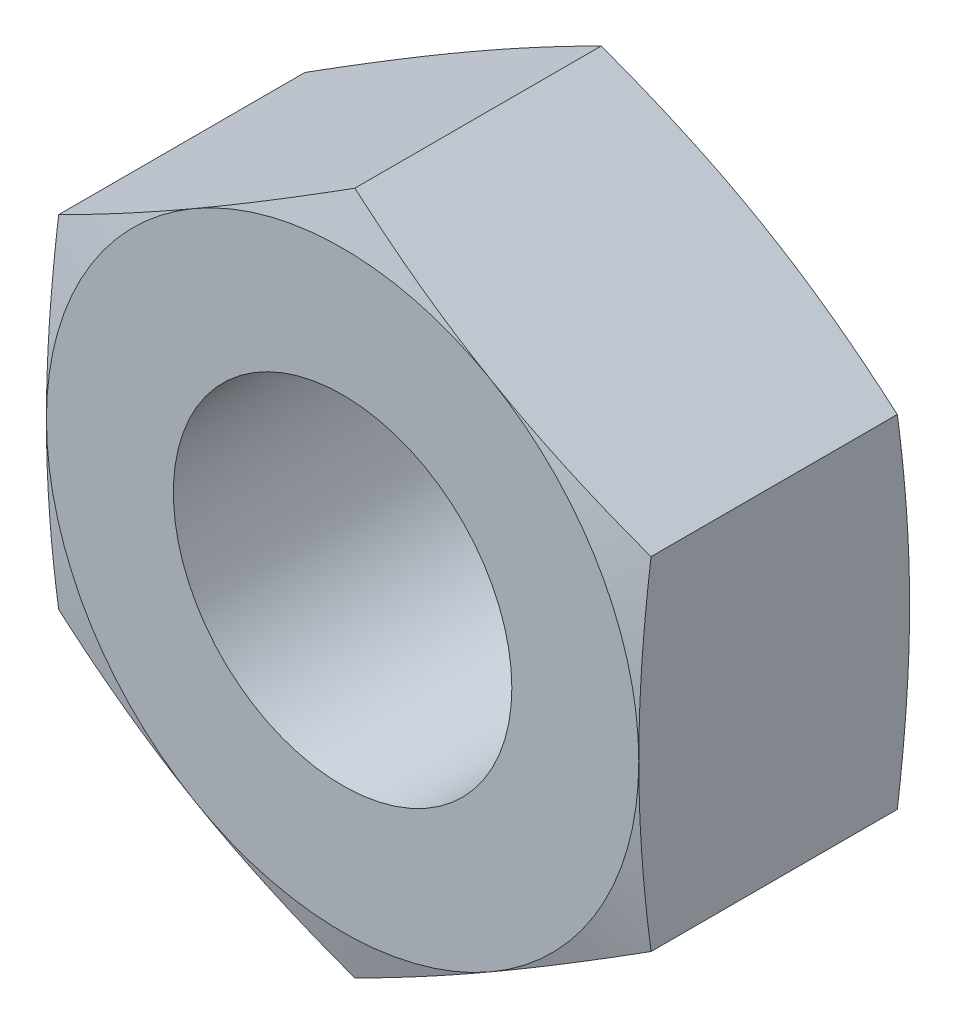
SolidWorks part; units mm, degrees
ref_plane "Front" through (0, 0, 0) normal (0, 0, 1) x (1, 0, 0)
ref_plane "Top" through (0, 0, 0) normal (0, 1, 0) x (1, 0, 0)
ref_plane "Right" through (0, 0, 0) normal (1, 0, 0) x (0, 0, -1)
sketch "Sketch1" plane through (0, 0, 0) normal (0, 0, 1) x (1, 0, 0)
  line L1 (0, 4.0415) -> (-3.5, 2.0207)
  line L2 (-3.5, 2.0207) -> (-3.5, -2.0207)
  line L3 (-3.5, -2.0207) -> (0, -4.0415)
  line L4 (0, -4.0415) -> (3.5, -2.0207)
  line L5 (3.5, -2.0207) -> (3.5, 2.0207)
  line L6 (3.5, 2.0207) -> (0, 4.0415)
  circle A0 centre (0, 0) radius 3.5 construction
  circle A1 centre (0, 0) radius 2
  dimension "D1" = 7
  dimension "D2" = 4
extrude "Boss-Extrude1" add sketch "Sketch1" along normal blind 3.2
sketch "Sketch2" plane through (0, 0, 0) normal (0, 1, 0) x (0, 0, -1)
  line L0 (-2.7981, -5) -> (-4.0038, -0.5)
  line L3 (-4.0038, -0.5) -> (-4.0038, -5)
  line L4 (-4.0038, -5) -> (-2.7981, -5)
  dimension "D1" = 15
  dimension "D2" = 0.5
  dimension "D3" = 5
sketch "Sketch3" plane through (0, 0, 0) normal (1, 0, 0) x (0, 0, -1)
  line L0 (2.8088, 0) -> (-4.7656, 0) construction
revolve "Cut-Revolve2" cut sketch "Sketch2" angle 360 about L0
ref_plane "Plane1" through (0, 0, 1.6) normal (0, 0, 1) x (1, 0, 0)
mirror "Mirror1" about plane through (0, 0, 1.6) normal (0, 0, 1) of "Cut-Revolve2"
